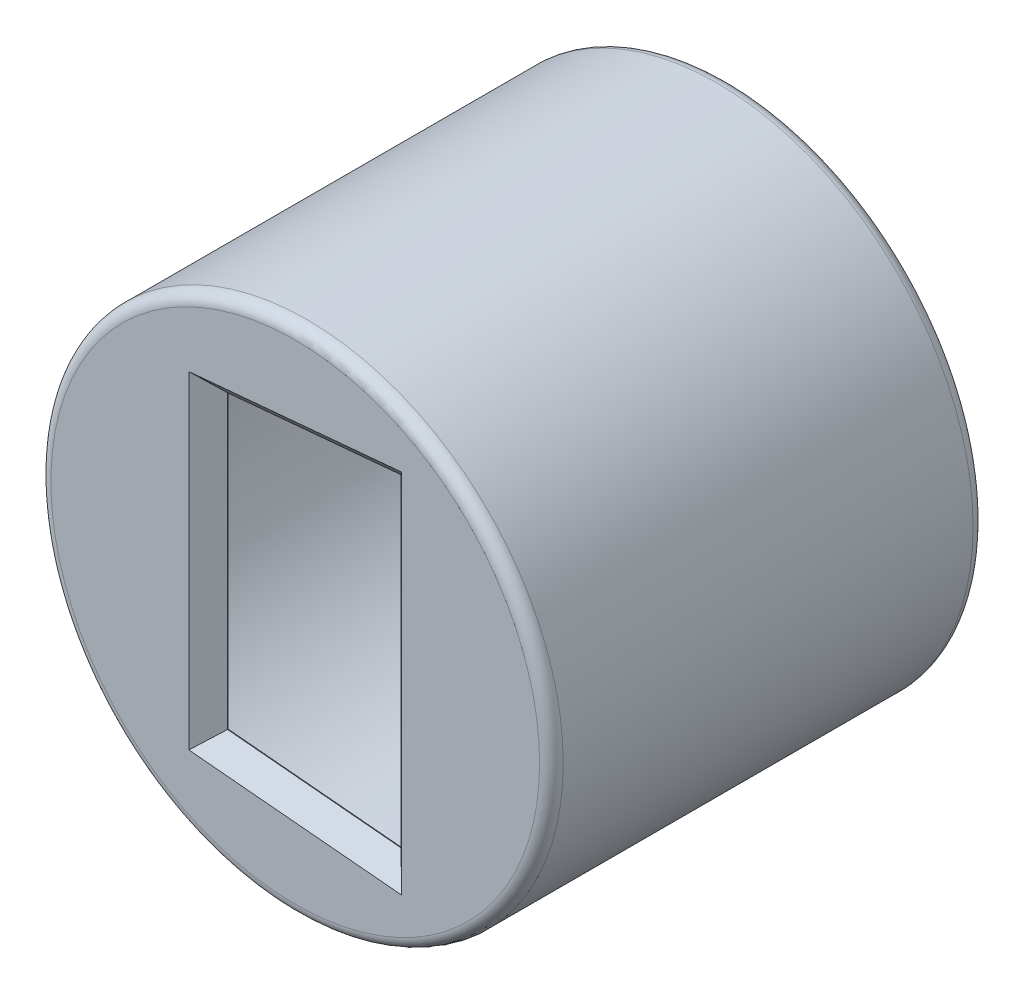
SolidWorks part; units mm, degrees
ref_plane "Front Plane" through (0, 0, 0) normal (0, 0, 1) x (1, 0, 0)
ref_plane "Top Plane" through (0, 0, 0) normal (0, 1, 0) x (1, 0, 0)
ref_plane "Right Plane" through (0, 0, 0) normal (1, 0, 0) x (0, 0, -1)
sketch "Sketch1" plane through (0, 0, 0) normal (0, 0, 1) x (1, 0, 0)
  circle A0 centre (0, 0) radius 6
  circle A1 centre (0, 0) radius 6.5
  dimension "D1" = 12
  dimension "D2" = 0.5
extrude "Boss-Extrude1" add sketch "Sketch1" along normal blind 10
sketch "Sketch2" plane through (0, 0, 0) normal (0, 0, -1) x (-1, 0, 0)
  circle A2 centre (0, 0) radius 6.5
extrude "Boss-Extrude2" add sketch "Sketch2" along normal blind 0.5
sketch "Sketch3" plane through (0, 0, 10) normal (0, 0, 1) x (1, 0, 0)
  line L0 (-2.2, 3.7) -> (-2.2, -3.7)
  line L5 (-4.3806, 4.7507) -> (4.0674, -4.411) construction
  line L6 (-2.2, -3.7) -> (2.2, 3.7) construction
  line L7 (2.2, 4.1) -> (2.2, -4.1)
  line L8 (2.2, -4.1) -> (-2.2, -3.7)
  line L9 (-2.2, 3.7) -> (2.2, 4.1)
  line L10 (0, -6.5) -> (0, 6.5) construction
  line L11 (-2.2, -3.7) -> (2.2, -3.7) construction
  line L12 (-6, 0) -> (6, 0) construction
  circle A0 centre (0, 0) radius 6.5
  circle A1 centre (0, 0) radius 6 construction
  circle A3 centre (0, 0) radius 6 construction
  point P17 (0, 0)
  dimension "D1" = 8.2
  dimension "D2" = 7.4
  dimension "D3" = 2.2
  dimension "D4" = 4.4
  dimension "D5" = 3.7
extrude "Boss-Extrude3" add sketch "Sketch3" along normal blind 0.5
chamfer "Chamfer1" distance 0.5 angle 44 4 edges at (2.2, 0, 10.5) (0, -3.9, 10.5) (0, 3.9, 10.5) (-2.2, 0, 10.5)
sketch "Sketch4" plane through (0, 0, -0.5) normal (0, 0, -1) x (-1, 0, 0)
  line L1 (-1.45, 1.8) -> (1.45, 1.8)
  line L2 (-1.45, 1.8) -> (-1.45, -1.8)
  line L3 (-1.45, -1.8) -> (1.45, -1.8)
  line L4 (1.45, 1.8) -> (1.45, -1.8)
  line L5 (-1.45, 1.8) -> (1.45, -1.8) construction
  line L6 (-1.45, -1.8) -> (1.45, 1.8) construction
  point P0 (0, 0)
  dimension "D1" = 3.6
  dimension "D2" = 2.9
extrude "Cut-Extrude1" cut sketch "Sketch4" against normal blind 1
fillet "Fillet1" radius 0.1 4 edges at (-1.45, -1.8, -0.25) (1.45, -1.8, -0.25) (1.45, 1.8, -0.25) (-1.45, 1.8, -0.25)
fillet "Fillet2" radius 0.3 2 edges at (-6.5, 0, -0.5) (6.5, 0, 10.5)
